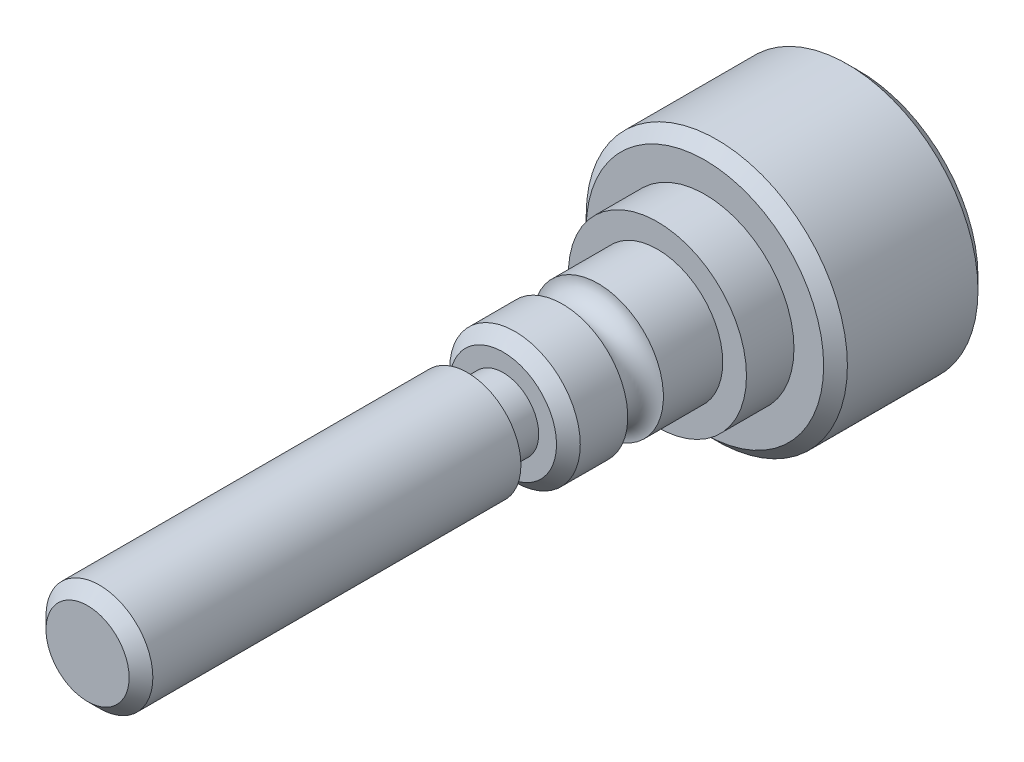
SolidWorks part; units mm, degrees
material "AISI 1045 Aço, trefilado"
ref_plane "Plano frontal" through (0, 0, 0) normal (0, 0, 1) x (1, 0, 0)
ref_plane "Plano superior" through (0, 0, 0) normal (0, 1, 0) x (1, 0, 0)
ref_plane "Plano direito" through (0, 0, 0) normal (1, 0, 0) x (0, 0, -1)
sketch "Esboço1" plane through (0, 0, 0) normal (0, 0, 1) x (1, 0, 0)
  circle A0 centre (0, 0) radius 11
  dimension "D1" = 22
extrude "Ressalto-extrusão1" add sketch "Esboço1" along normal blind 13
sketch "Esboço2" plane through (0, 0, 13) normal (0, 0, 1) x (1, 0, 0)
  circle A0 centre (0, 0) radius 7.5
  dimension "D1" = 15
extrude "Ressalto-extrusão2" add sketch "Esboço2" along normal blind 4
sketch "Esboço3" plane through (0, 0, 17) normal (0, 0, 1) x (1, 0, 0)
  circle A0 centre (0, 0) radius 5.5
  dimension "D1" = 11
extrude "Ressalto-extrusão3" add sketch "Esboço3" along normal blind 13 contours A0
ref_plane "Plano1" through (0, 0, 23.5) normal (0, 0, 1) x (1, 0, 0)
sketch "Esboço4" plane through (0, 0, 30) normal (0, 0, 1) x (1, 0, 0)
  circle A0 centre (0, 0) radius 3
  dimension "D1" = 6
extrude "Ressalto-extrusão4" add sketch "Esboço4" along normal blind 3
sketch "Esboço5" plane through (0, 0, 33) normal (0, 0, 1) x (1, 0, 0)
  circle A0 centre (0, 0) radius 4.5
  dimension "D1" = 9
extrude "Ressalto-extrusão5" add sketch "Esboço5" along normal blind 32
chamfer "Chanfro1" distance 1 angle 45 1 edges at (11, 0, 0)
chamfer "Chanfro2" distance 1 angle 45 3 edges at (4.5, 0, 65) (5.5, 0, 30) (11, 0, 13)
sketch "Esboço6" plane through (0, 0, 0) normal (0, 1, 0) x (1, 0, 0)
  line L0 (-8.25, -23.5) -> (8.25, -23.5) construction
  line L2 (-5.5, -17) -> (-5.5, -29) construction
  circle A0 centre (-5.5, -23.5) radius 1.5
  dimension "D1" = 0
  dimension "D2" = 0
sketch "Esboço7" plane through (0, 0, 23.5) normal (0, 0, 1) x (1, 0, 0)
  circle A0 centre (0, 0) radius 5.5
sweep "Varredura de corte1" cut profiles "Esboço6" path "Esboço7"
